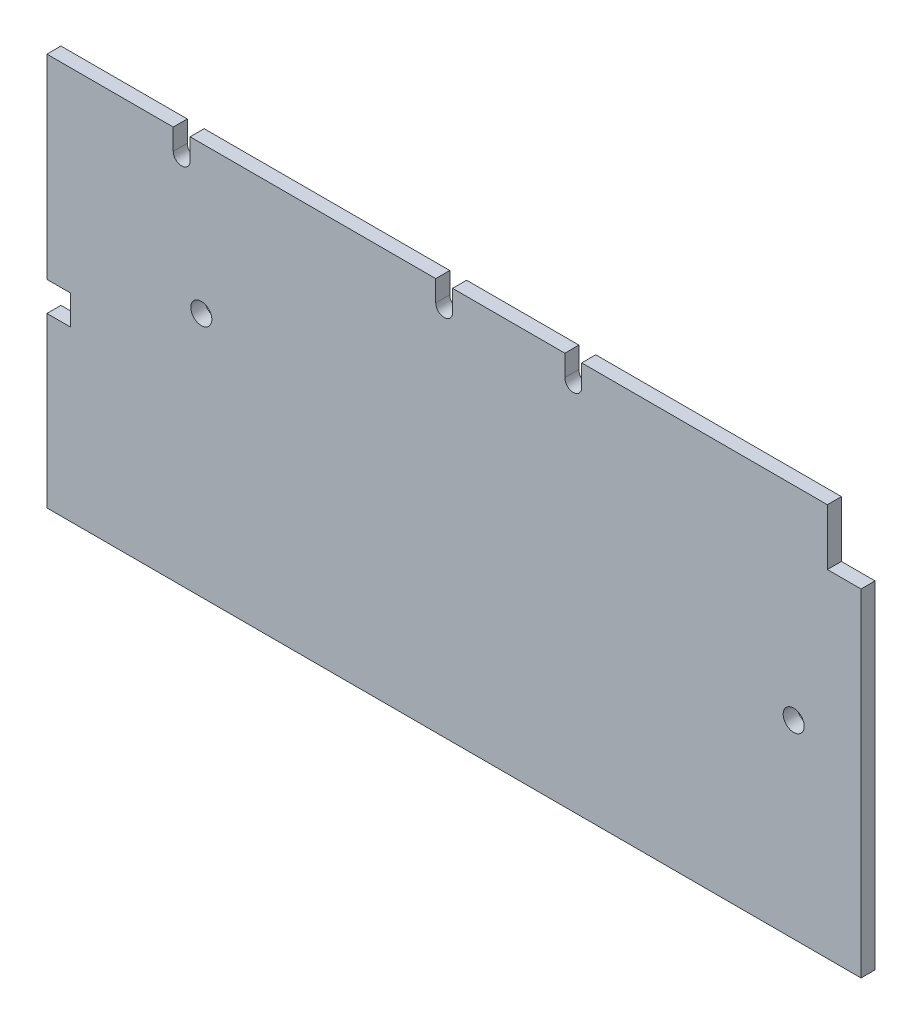
SolidWorks part; units mm, degrees
material "Плата системы питания"
ref_plane "Спереди" through (0, 0, 0) normal (0, 0, 1) x (1, 0, 0)
ref_plane "Сверху" through (0, 0, 0) normal (0, 1, 0) x (1, 0, 0)
ref_plane "Справа" through (0, 0, 0) normal (1, 0, 0) x (0, 0, -1)
sketch "Эскиз1" plane through (0, 0, 0) normal (0, 0, 1) x (1, 0, 0)
  line L0 (-13.5469, 13.4111) -> (-13.5469, 11.9111)
  line L1 (-22.5469, 13.4111) -> (35.4531, 13.4111)
  line L2 (-22.5469, 13.4111) -> (-22.5469, -14.5889)
  line L3 (-22.5469, -14.5889) -> (35.4531, -14.5889)
  line L4 (35.4531, 13.4111) -> (35.4531, -14.5889)
  line L5 (-12.3469, 13.4111) -> (-12.3469, 11.9111)
  line L6 (5.1531, 13.4111) -> (5.1531, 11.9111)
  line L7 (6.3531, 13.4111) -> (6.3531, 11.9111)
  line L8 (14.3531, 13.4111) -> (14.3531, 11.9111)
  line L9 (15.5531, 13.4111) -> (15.5531, 11.9111)
  line L10 (33.0531, 13.4111) -> (33.0531, 9.4111)
  line L11 (33.0531, 9.4111) -> (35.4531, 9.4111)
  line L12 (-22.5469, -0.4889) -> (-20.8831, -0.4889)
  line L13 (-20.8831, -0.4889) -> (-20.8831, -2.5889)
  line L14 (-20.8831, -2.5889) -> (-22.5469, -2.5889)
  circle A0 centre (-12.9469, 11.9111) radius 0.6
  circle A1 centre (5.7531, 11.9111) radius 0.6
  circle A2 centre (14.9531, 11.8875) radius 0.6005
  circle A3 centre (-11.5469, 2.9111) radius 0.75
  circle A4 centre (30.6531, -1.0889) radius 0.75
  point P24 (5.1531, 12.6611)
  point P25 (33.0531, 11.4111)
  dimension "D10" = 1.2
  dimension "D11" = 1.2
  dimension "D16" = 1.5
  dimension "D17" = 1.5
  dimension "D20" = 11
  dimension "D21" = 10.5
  dimension "D1" = 58
  dimension "D2" = 28
  dimension "D3" = 9
  dimension "D4" = 1.2
  dimension "D5" = 1.5
  dimension "D6" = 1.2
  dimension "D7" = 1.2
  dimension "D8" = 17.5
  dimension "D9" = 8
  dimension "D12" = 24
  dimension "D13" = 17.5
  dimension "D14" = 13.9
  dimension "D15" = 2.1
  dimension "D18" = 4.8
  dimension "D19" = 13.5
extrude "Бобышка-Вытянуть1" add sketch "Эскиз1" along normal blind 1 contours A2 L8 L1 L7 A1 L6 L5 A0 L0 L2 L3 L4 L9
